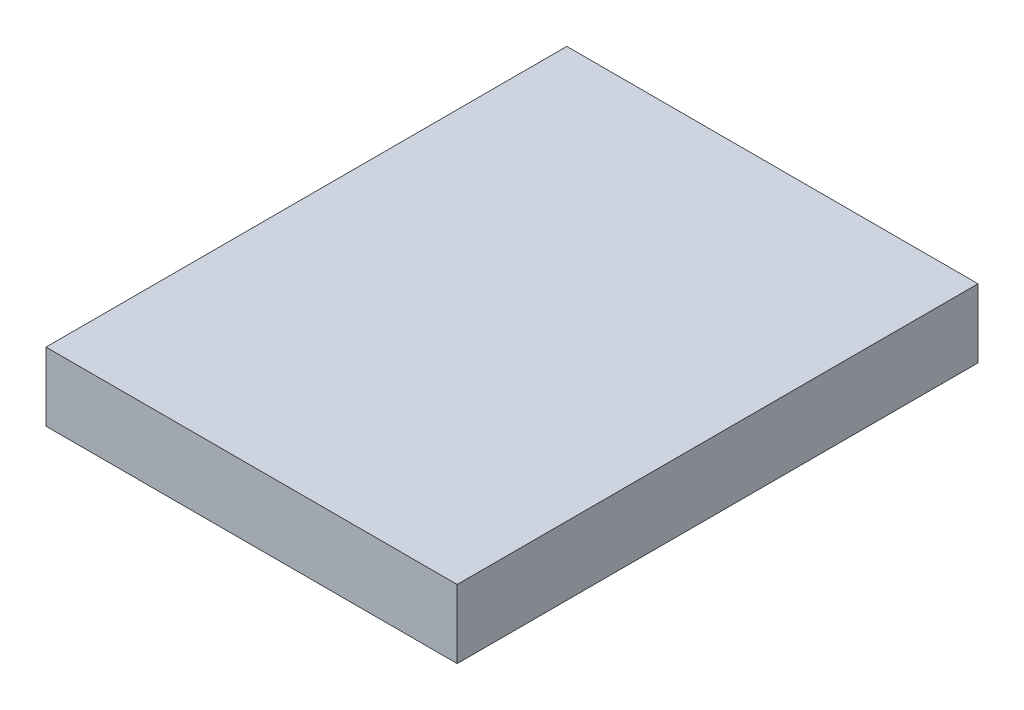
SolidWorks part; units mm, degrees
ref_plane "Front Plane" through (0, 0, 0) normal (0, 0, 1) x (1, 0, 0)
ref_plane "Top Plane" through (0, 0, 0) normal (0, 1, 0) x (1, 0, 0)
ref_plane "Right Plane" through (0, 0, 0) normal (1, 0, 0) x (0, 0, -1)
sketch "Sketch1" plane through (0, 0, 0) normal (0, 1, 0) x (1, 0, 0)
  line L1 (60, -76) -> (-60, -76)
  line L2 (60, -76) -> (60, 76)
  line L3 (60, 76) -> (-60, 76)
  line L4 (-60, -76) -> (-60, 76)
  line L5 (60, -76) -> (-60, 76) construction
  line L6 (60, 76) -> (-60, -76) construction
  point P0 (0, 0)
  dimension "D1" = 120
  dimension "D2" = 152
extrude "Boss-Extrude1" add sketch "Sketch1" along normal blind 20
equation "\"width\" = 120mm"
equation "\"height\"= 152mm"
equation "\"thick\"= 20mm"
equation "\"D1@Sketch1\"=\"width\""
equation "\"D2@Sketch1\"=\"height\""
equation "\"D1@Boss-Extrude1\"=\"thick\""
